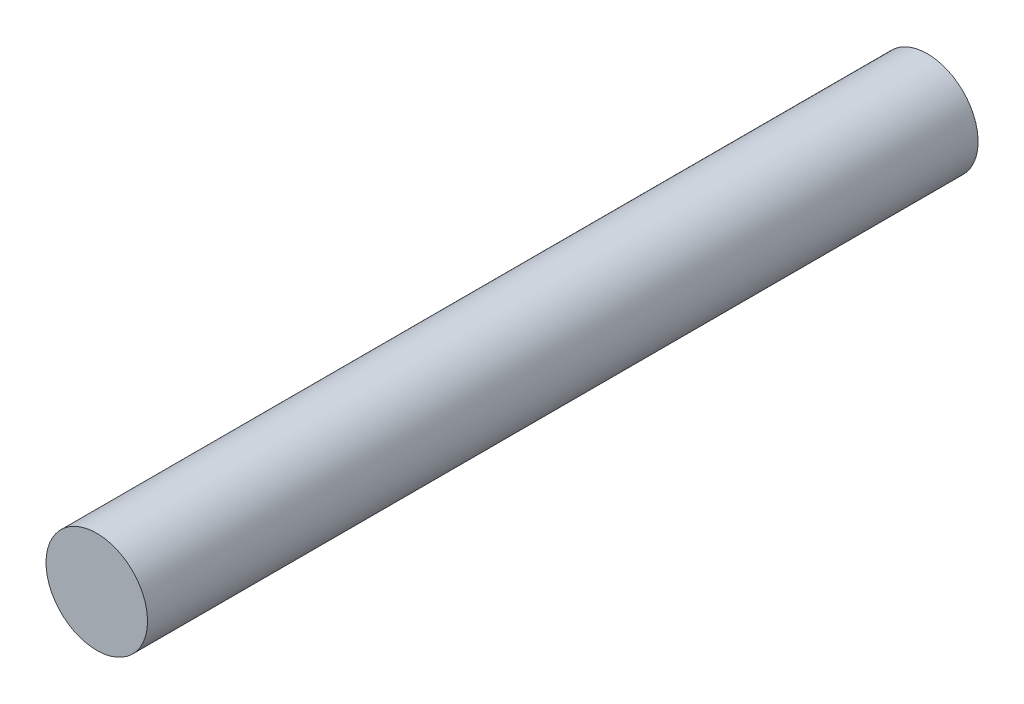
SolidWorks part; units mm, degrees
ref_plane "Alzado" through (0, 0, 0) normal (0, 0, 1) x (1, 0, 0)
ref_plane "Planta" through (0, 0, 0) normal (0, 1, 0) x (1, 0, 0)
ref_plane "Vista lateral" through (0, 0, 0) normal (1, 0, 0) x (0, 0, -1)
sketch "Croquis1" plane through (0, 0, 0) normal (0, 0, 1) x (1, 0, 0)
  circle A0 centre (0, 0) radius 2.75
  dimension "D1" = 5.5
extrude "Saliente-Extruir1" add sketch "Croquis1" along normal blind 45
